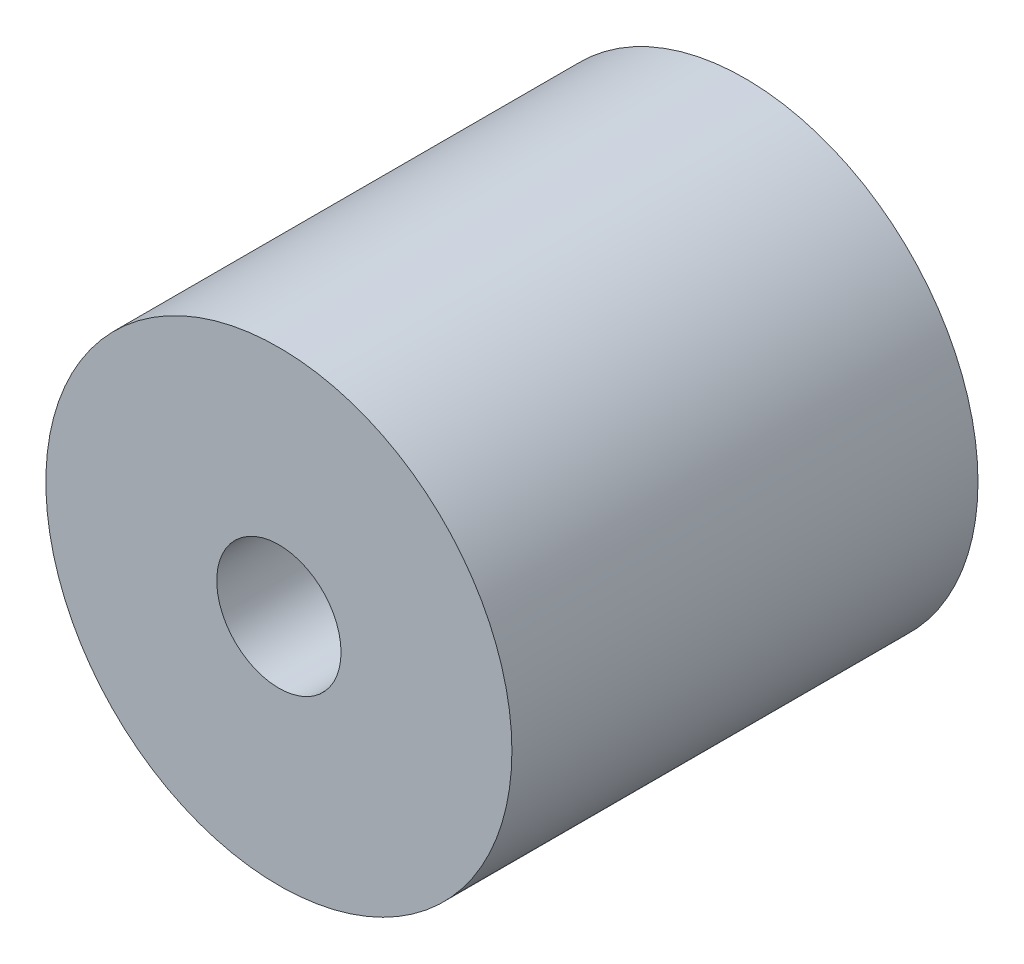
SolidWorks part; units mm, degrees
ref_plane "Front Plane" through (0, 0, 0) normal (0, 0, 1) x (1, 0, 0)
ref_plane "Top Plane" through (0, 0, 0) normal (0, 1, 0) x (1, 0, 0)
ref_plane "Right Plane" through (0, 0, 0) normal (1, 0, 0) x (0, 0, -1)
sketch "Sketch1" plane through (0, 0, 0) normal (0, 0, 1) x (1, 0, 0)
  circle A0 centre (0, 0) radius 15
extrude "Extrude1" add sketch "Sketch1" along normal mid plane 30
sketch "Sketch2" plane through (0, 0, 0) normal (0, 0, 1) x (1, 0, 0)
  circle A0 centre (0, 0) radius 4
extrude "Cut-Extrude1" cut sketch "Sketch2" against normal mid plane 30
